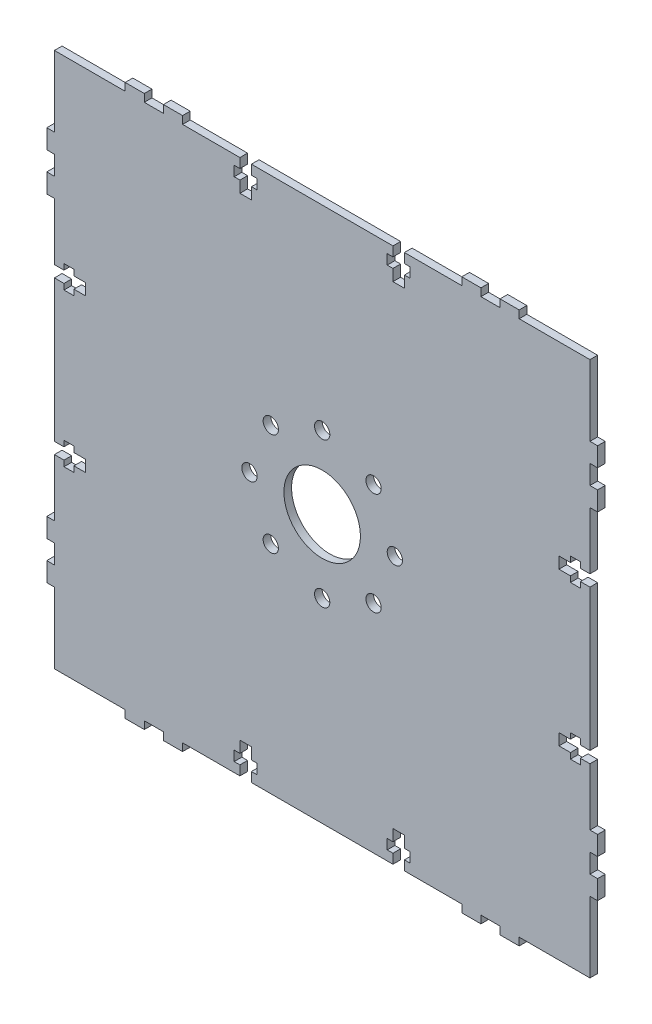
SolidWorks part; units mm, degrees
ref_plane "前视基准面" through (0, 0, 0) normal (0, 0, 1) x (1, 0, 0)
ref_plane "上视基准面" through (0, 0, 0) normal (0, 1, 0) x (1, 0, 0)
ref_plane "右视基准面" through (0, 0, 0) normal (1, 0, 0) x (0, 0, -1)
sketch "草图1" plane through (0, 0, 0) normal (0, 0, 1) x (1, 0, 0)
  line L50 (249.9534, 275.9629) -> (249.9534, 255.9629) construction
  line L53 (317.4534, 257.4629) -> (317.4534, 258.9629)
  line L54 (317.4534, 254.4629) -> (317.4534, 252.9629)
  line L55 (319.9534, 254.4629) -> (317.4534, 254.4629)
  line L56 (317.4534, 258.9629) -> (314.8534, 258.9629)
  line L57 (314.8534, 258.9629) -> (314.8534, 257.4629)
  line L58 (314.8534, 257.4629) -> (311.8534, 257.4629)
  line L59 (311.8534, 254.4629) -> (311.8534, 257.4629)
  line L60 (314.8534, 254.4629) -> (311.8534, 254.4629)
  line L61 (314.8534, 252.9629) -> (314.8534, 254.4629)
  line L62 (317.4534, 252.9629) -> (314.8534, 252.9629)
  line L63 (317.4534, 257.4629) -> (319.9534, 257.4629)
  line L68 (319.9534, 254.4629) -> (319.9534, 257.4629) construction
  line L69 (311.8534, 255.9629) -> (319.9534, 255.9629) construction
  line L71 (269.9534, 275.9629) -> (249.9534, 275.9629) construction
  line L73 (311.8534, 295.9629) -> (319.9534, 295.9629) construction
  line L75 (317.4534, 294.4629) -> (319.9534, 294.4629)
  line L76 (317.4534, 298.9629) -> (314.8534, 298.9629)
  line L77 (314.8534, 298.9629) -> (314.8534, 297.4629)
  line L78 (314.8534, 297.4629) -> (311.8534, 297.4629)
  line L79 (311.8534, 297.4629) -> (311.8534, 294.4629)
  line L80 (314.8534, 294.4629) -> (311.8534, 294.4629)
  line L81 (314.8534, 292.9629) -> (314.8534, 294.4629)
  line L82 (317.4534, 292.9629) -> (314.8534, 292.9629)
  line L83 (319.9534, 297.4629) -> (317.4534, 297.4629)
  line L84 (317.4534, 297.4629) -> (317.4534, 298.9629)
  line L85 (317.4534, 294.4629) -> (317.4534, 292.9629)
  line L86 (231.4534, 208.4629) -> (232.9534, 208.4629)
  line L87 (228.4534, 208.4629) -> (226.9534, 208.4629)
  line L88 (228.4534, 205.9629) -> (228.4534, 208.4629)
  line L89 (232.9534, 208.4629) -> (232.9534, 211.0629)
  line L90 (232.9534, 211.0629) -> (231.4534, 211.0629)
  line L91 (231.4534, 211.0629) -> (231.4534, 214.0629)
  line L92 (228.4534, 214.0629) -> (231.4534, 214.0629)
  line L93 (228.4534, 211.0629) -> (228.4534, 214.0629)
  line L94 (226.9534, 211.0629) -> (228.4534, 211.0629)
  line L95 (226.9534, 208.4629) -> (226.9534, 211.0629)
  line L96 (231.4534, 208.4629) -> (231.4534, 205.9629)
  line L97 (268.4534, 208.4629) -> (268.4534, 205.9629)
  line L98 (272.9534, 208.4629) -> (272.9534, 211.0629)
  line L99 (272.9534, 211.0629) -> (271.4534, 211.0629)
  line L100 (271.4534, 211.0629) -> (271.4534, 214.0629)
  line L101 (271.4534, 214.0629) -> (268.4534, 214.0629)
  line L102 (268.4534, 211.0629) -> (268.4534, 214.0629)
  line L103 (266.9534, 211.0629) -> (268.4534, 211.0629)
  line L104 (266.9534, 208.4629) -> (266.9534, 211.0629)
  line L105 (271.4534, 205.9629) -> (271.4534, 208.4629)
  line L106 (271.4534, 208.4629) -> (272.9534, 208.4629)
  line L107 (268.4534, 208.4629) -> (266.9534, 208.4629)
  line L108 (228.4534, 205.9629) -> (231.4534, 205.9629) construction
  line L109 (229.9534, 214.0629) -> (229.9534, 205.9629) construction
  line L110 (269.9534, 214.0629) -> (269.9534, 205.9629) construction
  line L111 (182.4534, 294.4629) -> (182.4534, 292.9629)
  line L112 (182.4534, 297.4629) -> (182.4534, 298.9629)
  line L113 (179.9534, 297.4629) -> (182.4534, 297.4629)
  line L114 (182.4534, 292.9629) -> (185.0534, 292.9629)
  line L115 (185.0534, 292.9629) -> (185.0534, 294.4629)
  line L116 (185.0534, 294.4629) -> (188.0534, 294.4629)
  line L117 (188.0534, 297.4629) -> (188.0534, 294.4629)
  line L118 (185.0534, 297.4629) -> (188.0534, 297.4629)
  line L119 (185.0534, 298.9629) -> (185.0534, 297.4629)
  line L120 (182.4534, 298.9629) -> (185.0534, 298.9629)
  line L121 (182.4534, 294.4629) -> (179.9534, 294.4629)
  line L122 (182.4534, 257.4629) -> (179.9534, 257.4629)
  line L123 (182.4534, 252.9629) -> (185.0534, 252.9629)
  line L124 (185.0534, 252.9629) -> (185.0534, 254.4629)
  line L125 (185.0534, 254.4629) -> (188.0534, 254.4629)
  line L126 (188.0534, 254.4629) -> (188.0534, 257.4629)
  line L127 (185.0534, 257.4629) -> (188.0534, 257.4629)
  line L128 (185.0534, 258.9629) -> (185.0534, 257.4629)
  line L129 (182.4534, 258.9629) -> (185.0534, 258.9629)
  line L130 (179.9534, 254.4629) -> (182.4534, 254.4629)
  line L131 (182.4534, 254.4629) -> (182.4534, 252.9629)
  line L132 (182.4534, 257.4629) -> (182.4534, 258.9629)
  line L133 (179.9534, 297.4629) -> (179.9534, 294.4629) construction
  line L134 (188.0534, 295.9629) -> (179.9534, 295.9629) construction
  line L135 (188.0534, 255.9629) -> (179.9534, 255.9629) construction
  line L136 (268.4534, 343.4629) -> (266.9534, 343.4629)
  line L137 (271.4534, 343.4629) -> (272.9534, 343.4629)
  line L138 (271.4534, 345.9629) -> (271.4534, 343.4629)
  line L139 (266.9534, 343.4629) -> (266.9534, 340.8629)
  line L140 (266.9534, 340.8629) -> (268.4534, 340.8629)
  line L141 (268.4534, 340.8629) -> (268.4534, 337.8629)
  line L142 (271.4534, 337.8629) -> (268.4534, 337.8629)
  line L143 (271.4534, 340.8629) -> (271.4534, 337.8629)
  line L144 (272.9534, 340.8629) -> (271.4534, 340.8629)
  line L145 (272.9534, 343.4629) -> (272.9534, 340.8629)
  line L146 (268.4534, 343.4629) -> (268.4534, 345.9629)
  line L147 (231.4534, 343.4629) -> (231.4534, 345.9629)
  line L148 (226.9534, 343.4629) -> (226.9534, 340.8629)
  line L149 (226.9534, 340.8629) -> (228.4534, 340.8629)
  line L150 (228.4534, 340.8629) -> (228.4534, 337.8629)
  line L151 (228.4534, 337.8629) -> (231.4534, 337.8629)
  line L152 (231.4534, 340.8629) -> (231.4534, 337.8629)
  line L153 (232.9534, 340.8629) -> (231.4534, 340.8629)
  line L154 (232.9534, 343.4629) -> (232.9534, 340.8629)
  line L155 (228.4534, 345.9629) -> (228.4534, 343.4629)
  line L156 (228.4534, 343.4629) -> (226.9534, 343.4629)
  line L157 (231.4534, 343.4629) -> (232.9534, 343.4629)
  line L158 (271.4534, 345.9629) -> (268.4534, 345.9629) construction
  line L159 (269.9534, 337.8629) -> (269.9534, 345.9629) construction
  line L160 (229.9534, 337.8629) -> (229.9534, 345.9629) construction
  line L163 (179.9534, 294.4629) -> (179.9534, 257.4629)
  line L169 (268.4534, 345.9629) -> (231.4534, 345.9629)
  line L172 (319.9534, 257.4629) -> (319.9534, 294.4629)
  line L175 (231.4534, 205.9629) -> (268.4534, 205.9629)
  line L188 (179.9534, 239.4629) -> (177.9534, 239.4629)
  line L189 (177.9534, 239.4629) -> (177.9534, 234.4629)
  line L190 (177.9534, 234.4629) -> (179.9534, 234.4629)
  line L191 (179.9534, 234.4629) -> (179.9534, 229.4629)
  line L192 (179.9534, 229.4629) -> (177.9534, 229.4629)
  line L193 (177.9534, 229.4629) -> (177.9534, 224.4629)
  line L194 (177.9534, 224.4629) -> (179.9534, 224.4629)
  line L195 (179.9534, 224.4629) -> (179.9534, 205.9629)
  line L196 (179.9534, 327.4629) -> (179.9534, 345.9629)
  line L197 (177.9534, 327.4629) -> (179.9534, 327.4629)
  line L198 (177.9534, 322.4629) -> (177.9534, 327.4629)
  line L199 (179.9534, 322.4629) -> (177.9534, 322.4629)
  line L200 (179.9534, 317.4629) -> (179.9534, 322.4629)
  line L201 (177.9534, 317.4629) -> (179.9534, 317.4629)
  line L202 (177.9534, 312.4629) -> (177.9534, 317.4629)
  line L203 (179.9534, 312.4629) -> (177.9534, 312.4629)
  line L206 (213.4534, 345.9629) -> (213.4534, 347.9629)
  line L207 (213.4534, 347.9629) -> (208.4534, 347.9629)
  line L208 (208.4534, 347.9629) -> (208.4534, 345.9629)
  line L209 (208.4534, 345.9629) -> (203.4534, 345.9629)
  line L210 (203.4534, 345.9629) -> (203.4534, 347.9629)
  line L211 (203.4534, 347.9629) -> (198.4534, 347.9629)
  line L212 (198.4534, 347.9629) -> (198.4534, 345.9629)
  line L213 (198.4534, 345.9629) -> (179.9534, 345.9629)
  line L214 (301.4534, 345.9629) -> (319.9534, 345.9629)
  line L215 (301.4534, 347.9629) -> (301.4534, 345.9629)
  line L216 (296.4534, 347.9629) -> (301.4534, 347.9629)
  line L217 (296.4534, 345.9629) -> (296.4534, 347.9629)
  line L218 (291.4534, 345.9629) -> (296.4534, 345.9629)
  line L219 (291.4534, 347.9629) -> (291.4534, 345.9629)
  line L220 (286.4534, 347.9629) -> (291.4534, 347.9629)
  line L221 (286.4534, 345.9629) -> (286.4534, 347.9629)
  line L224 (319.9534, 312.4629) -> (321.9534, 312.4629)
  line L225 (321.9534, 312.4629) -> (321.9534, 317.4629)
  line L226 (321.9534, 317.4629) -> (319.9534, 317.4629)
  line L227 (319.9534, 317.4629) -> (319.9534, 322.4629)
  line L228 (319.9534, 322.4629) -> (321.9534, 322.4629)
  line L229 (321.9534, 322.4629) -> (321.9534, 327.4629)
  line L230 (321.9534, 327.4629) -> (319.9534, 327.4629)
  line L231 (319.9534, 327.4629) -> (319.9534, 345.9629)
  line L232 (319.9534, 224.4629) -> (319.9534, 205.9629)
  line L233 (321.9534, 224.4629) -> (319.9534, 224.4629)
  line L234 (321.9534, 229.4629) -> (321.9534, 224.4629)
  line L235 (319.9534, 229.4629) -> (321.9534, 229.4629)
  line L236 (319.9534, 234.4629) -> (319.9534, 229.4629)
  line L237 (321.9534, 234.4629) -> (319.9534, 234.4629)
  line L238 (321.9534, 239.4629) -> (321.9534, 234.4629)
  line L239 (319.9534, 239.4629) -> (321.9534, 239.4629)
  line L242 (286.4534, 205.9629) -> (286.4534, 203.9629)
  line L243 (286.4534, 203.9629) -> (291.4534, 203.9629)
  line L244 (291.4534, 203.9629) -> (291.4534, 205.9629)
  line L245 (291.4534, 205.9629) -> (296.4534, 205.9629)
  line L246 (296.4534, 205.9629) -> (296.4534, 203.9629)
  line L247 (296.4534, 203.9629) -> (301.4534, 203.9629)
  line L248 (301.4534, 203.9629) -> (301.4534, 205.9629)
  line L249 (301.4534, 205.9629) -> (319.9534, 205.9629)
  line L250 (198.4534, 205.9629) -> (179.9534, 205.9629)
  line L251 (198.4534, 203.9629) -> (198.4534, 205.9629)
  line L252 (203.4534, 203.9629) -> (198.4534, 203.9629)
  line L253 (203.4534, 205.9629) -> (203.4534, 203.9629)
  line L254 (208.4534, 205.9629) -> (203.4534, 205.9629)
  line L255 (208.4534, 203.9629) -> (208.4534, 205.9629)
  line L256 (213.4534, 203.9629) -> (208.4534, 203.9629)
  line L257 (213.4534, 205.9629) -> (213.4534, 203.9629)
  line L268 (179.9534, 297.4629) -> (179.9534, 312.4629)
  line L269 (213.4534, 345.9629) -> (228.4534, 345.9629)
  line L270 (271.4534, 345.9629) -> (286.4534, 345.9629)
  line L271 (319.9534, 312.4629) -> (319.9534, 297.4629)
  line L272 (319.9534, 254.4629) -> (319.9534, 239.4629)
  line L273 (286.4534, 205.9629) -> (271.4534, 205.9629)
  line L274 (213.4534, 205.9629) -> (228.4534, 205.9629)
  line L275 (179.9534, 239.4629) -> (179.9534, 254.4629)
  circle A14 centre (249.9534, 275.9629) radius 10
  circle A15 centre (249.9534, 275.9629) radius 19 construction
  circle A16 centre (230.9534, 275.9629) radius 2
  circle A17 centre (236.5183, 289.398) radius 2
  circle A18 centre (249.9534, 294.9629) radius 2
  circle A19 centre (263.3884, 289.398) radius 2
  circle A20 centre (268.9534, 275.9629) radius 2
  circle A21 centre (263.3884, 262.5279) radius 2
  circle A22 centre (249.9534, 256.9629) radius 2
  circle A23 centre (236.5183, 262.5279) radius 2
  dimension "D1" = 8
  dimension "D5" = 4
  dimension "D4" = 4
  dimension "D2" = 20
extrude "凸台-拉伸1" add sketch "草图1" along normal blind 2
sketch "草图2" plane through (179.9534, 0, 0) normal (-1, 0, 0) x (0, 0, 1)
  line L0 (1, 294.4629) -> (1, 297.4629) construction
  line L1 (2, 294.4629) -> (0, 294.4629) construction
  line L2 (2, 297.4629) -> (0, 297.4629) construction
  line L3 (1, 295.9629) -> (1, 312.4629) construction
  line L4 (2, 312.4629) -> (0, 312.4629) construction
  circle A0 centre (1, 295.9629) radius 1.5
sketch "草图3" plane through (0, 345.9629, 0) normal (0, 1, 0) x (1, 0, 0)
  line L0 (228.4534, -1) -> (231.4534, -1)
  line L1 (228.4534, -2) -> (228.4534, 0) construction
  line L2 (231.4534, -2) -> (231.4534, 0) construction
  circle A0 centre (229.9534, -1) radius 1.5
sketch "草图4" plane through (319.9534, 0, 0) normal (1, 0, 0) x (0, 0, -1)
  line L0 (-1, 257.4629) -> (-1, 254.4629) construction
  line L1 (-2, 257.4629) -> (0, 257.4629) construction
  line L2 (-2, 254.4629) -> (0, 254.4629) construction
  circle A0 centre (-1, 255.9629) radius 1.5
sketch "草图5" plane through (0, 205.9629, 0) normal (0, -1, 0) x (1, 0, 0)
  line L0 (231.4534, 1) -> (228.4534, 1) construction
  line L1 (231.4534, 2) -> (231.4534, 0) construction
  line L2 (228.4534, 2) -> (228.4534, 0) construction
  circle A0 centre (229.9534, 1) radius 1.5
